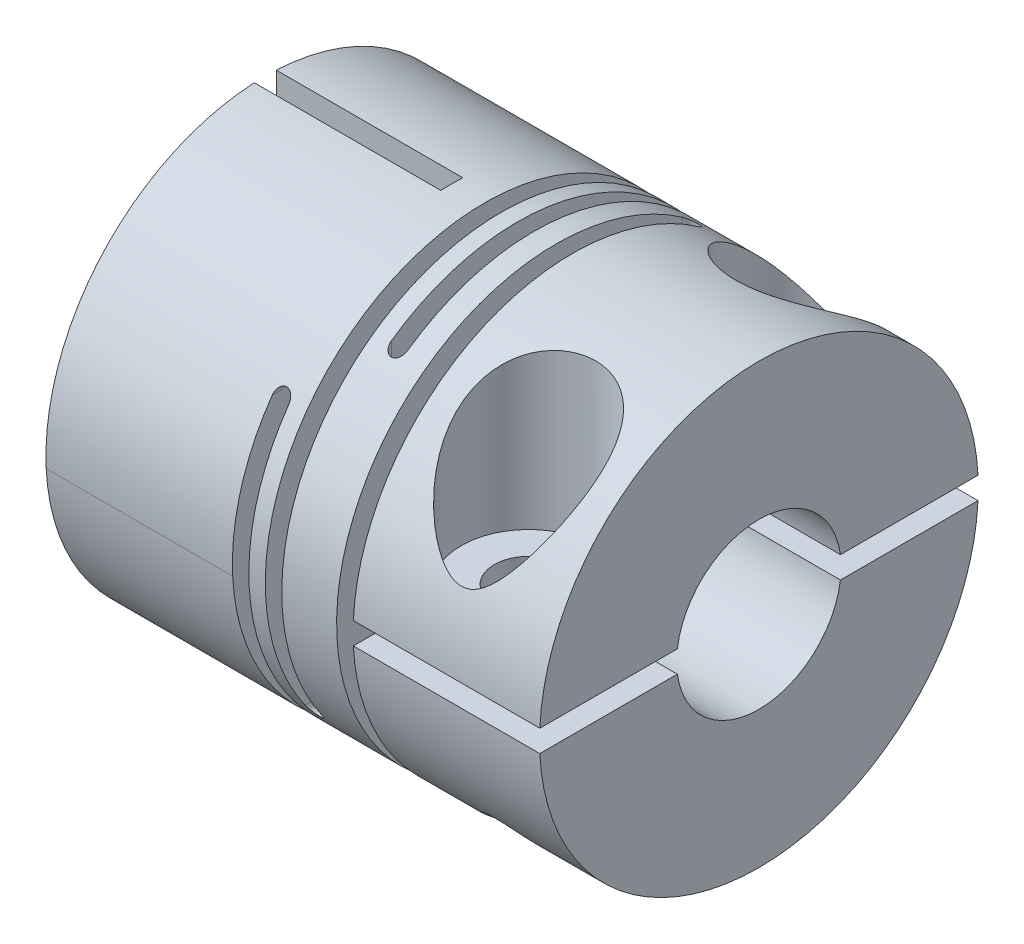
SolidWorks part; units mm, degrees
ref_plane "前视基准面" through (0, 0, 0) normal (0, 0, 1) x (1, 0, 0)
ref_plane "上视基准面" through (0, 0, 0) normal (0, 1, 0) x (1, 0, 0)
ref_plane "右视基准面" through (0, 0, 0) normal (1, 0, 0) x (0, 0, -1)
other "Configuration Table"
sketch "草图6" plane through (0, 0, 0) normal (1, 0, 0) x (0, 0, -1)
  circle A0 centre (0, 0) radius 8
  dimension "D1" = 16
extrude "凸台-拉伸4" add sketch "草图6" along normal blind 18
sketch "草图8" plane through (0, 0, 0) normal (0, 0, 1) x (1, 0, 0)
  line L0 (7.1, 4.6) -> (7.1, -8.7196) construction
  line L1 (7.4, 4.6) -> (7.4, -8.7196)
  line L2 (6.8, 4.6) -> (6.8, -8.7196)
  line L3 (8.3, 9.9177) -> (8.3, -4.6) construction
  line L4 (8.6, 9.9177) -> (8.6, -4.6)
  line L5 (8, 9.9177) -> (8, -4.6)
  line L6 (0, 8) -> (0, -8) construction
  line L7 (0, 0) -> (20.3451, 0) construction
  arc A0 (7.4, 4.6) -> (6.8, 4.6) centre (7.1, 4.6) ccw
  arc A1 (6.8, -8.7196) -> (7.4, -8.7196) centre (7.1, -8.7196) ccw
  arc A2 (8.6, 9.9177) -> (8, 9.9177) centre (8.3, 9.9177) ccw
  arc A3 (8, -4.6) -> (8.6, -4.6) centre (8.3, -4.6) ccw
  point P2 (7.1, -2.0598)
  point P9 (8.3, 2.6589)
  dimension "D1" = 6.8
  dimension "D2" = 0.6
  dimension "D3" = 0.6
  dimension "D4" = 1.2
  dimension "D5" = 4.6
  dimension "D6" = 4.6
extrude "切除-拉伸1" cut sketch "草图8" against normal through all both and the other way through all
sketch "草图9" plane through (0, 0, 0) normal (0, 1, 0) x (1, 0, 0)
  line L0 (0, 0) -> (19.4872, 0) construction
  line L1 (9.5, 9.7846) -> (9.5, -4.6) construction
  line L2 (9.8, 9.7846) -> (9.8, -4.6)
  line L3 (9.2, 9.7846) -> (9.2, -4.6)
  line L4 (10.9, 4.6) -> (10.9, -8.9267) construction
  line L5 (11.2, 4.6) -> (11.2, -8.9267)
  line L6 (10.6, 4.6) -> (10.6, -8.9267)
  line L7 (18, -8) -> (18, 8) construction
  arc A0 (9.8, 9.7846) -> (9.2, 9.7846) centre (9.5, 9.7846) ccw
  arc A1 (9.2, -4.6) -> (9.8, -4.6) centre (9.5, -4.6) ccw
  arc A2 (11.2, 4.6) -> (10.6, 4.6) centre (10.9, 4.6) ccw
  arc A3 (10.6, -8.9267) -> (11.2, -8.9267) centre (10.9, -8.9267) ccw
  point P5 (9.5, 2.5923)
  point P12 (10.9, -2.1633)
  dimension "D1" = 0.6
  dimension "D2" = 0.6
  dimension "D3" = 4.6
  dimension "D4" = 4.6
  dimension "D5" = 6.8
  dimension "D6" = 1.4
extrude "切除-拉伸2" cut sketch "草图9" against normal through all both and the other way through all
sketch "草图10" plane through (0, 0, 0) normal (0, 0, 1) x (1, 0, 0)
  line L0 (0, 0) -> (19.2209, 0) construction
  line L1 (11.2, 8) -> (11.2, -8) construction
  line L2 (11.2, 0.4) -> (18, 0.4)
  line L3 (11.2, 0.4) -> (11.2, -0.4)
  line L4 (11.2, -0.4) -> (18, -0.4)
  line L5 (18, 0.4) -> (18, -0.4)
  line L6 (18, -8) -> (18, 8) construction
  dimension "D1" = 0.8
extrude "切除-拉伸3" cut sketch "草图10" against normal through all both and the other way through all
sketch "草图11" plane through (0, 0, 0) normal (0, 1, 0) x (1, 0, 0)
  line L0 (0, 0) -> (13.7629, 0) construction
  line L1 (0, 8) -> (0, -8) construction
  line L2 (0, 0.4) -> (6.8, 0.4)
  line L3 (0, 0.4) -> (0, -0.4)
  line L4 (0, -0.4) -> (6.8, -0.4)
  line L5 (6.8, 0.4) -> (6.8, -0.4)
  line L6 (6.8, 6.5452) -> (6.8, -6.5452) construction
  dimension "D1" = 0.8
extrude "切除-拉伸4" cut sketch "草图11" against normal through all both and the other way through all
sketch "草图12" plane through (0, 0, 0) normal (-1, 0, 0) x (0, 0, 1)
  circle A0 centre (0, 0) radius 2.5
  dimension "D1" = 5
extrude "切除-拉伸6" cut sketch "草图12" against normal up to vertex (6.8 mm away)
sketch "草图14" plane through (18, 0, 0) normal (1, 0, 0) x (0, 0, -1)
  circle A0 centre (0, 0) radius 3
  dimension "D1" = 6
extrude "切除-拉伸7" cut sketch "草图14" against normal up to vertex (6.8 mm away)
ref_plane "基准面3" through (0, 8, 0) normal (0, 1, 0) x (1, 0, 0)
hole_wizard "M2.5 六角圆柱头螺钉的柱形沉头孔2" positions "草图23" profile "草图24" counterbore size "M2.5" standard "GB" end condition up to next
sketch "草图23" plane through (0, 8, 0) normal (0, 1, 0) x (1, 0, 0)
  line L0 (0, 0) -> (24.0341, 0) construction
  line L4 (18, -7.99) -> (18, 7.99) construction
  point P0 (14.6, 5)
  point P2 (14.6, -5)
  point P14 (14.6622, 7.99)
  point P21 (17.8838, 5.6541)
  point P24 (0, 0)
  dimension "D1" = 10
  dimension "D2" = 3.4
sketch "草图24" plane through (14.6, 8, -5) normal (1, 0, 0) x (0, 0, 1)
  line L0 (0, 0) -> (0, 7.6)
  line L1 (0, 7.6) -> (1.25, 7.6)
  line L3 (1.25, 7.6) -> (1.25, 6.25)
  line L4 (2.45, 6.25) -> (1.25, 6.25)
  line L5 (2.45, 6.25) -> (2.45, 0.075)
  line L6 (2.45, 0.075) -> (2.525, 0)
  line L7 (2.525, 0) -> (0, 0)
  line L8 (-2.45, 0.075) -> (-2.525, 0) construction
  line L11 (0, -6.35) -> (0, 107.95) construction
  dimension "通孔孔直径" = 2.5
  dimension "通孔孔深度" = 7.6
  dimension "柱形沉头孔直径" = 4.9
  dimension "柱形沉头孔深度" = 6.25
  dimension "近端锥形沉头孔直径" = 5.05
  dimension "近端锥形沉头孔角度" = 90
ref_plane "基准面4" through (0, -8, 0) normal (0, -1, 0) x (-1, 0, 0)
hole_wizard "M2.5 螺纹孔1" positions "草图25" profile "草图26" tap size "M2.5" standard "GB" end condition up to next
sketch "草图25" plane through (0, -8, 0) normal (0, -1, 0) x (-1, 0, 0)
  point P0 (-14.6, 5)
  point P3 (-14.6, -5)
sketch "草图26" plane through (14.6, -8, -5) normal (1, 0, 0) x (0, 0, -1)
  line L0 (0, 0) -> (0, 7.6)
  line L1 (0, 7.6) -> (1.025, 7.6)
  line L2 (1.025, 7.6) -> (1.025, 0.25)
  line L3 (1.025, 0.25) -> (1.275, 0)
  line L5 (1.275, 0) -> (0, 0)
  line L6 (-1.025, 0.25) -> (-1.275, 0) construction
  line L11 (0, -6.35) -> (0, 107.95) construction
  dimension "通孔螺纹孔钻头直径" = 2.05
  dimension "通孔螺纹孔钻头深度" = 7.6
  dimension "近端锥形沉头孔直径" = 2.55
  dimension "近端锥形沉头孔角度" = 90
cosmetic thread "孔螺纹线1"
cosmetic thread "孔螺纹线2"
sketch "草图27" plane through (0, -8, 0) normal (0, -1, 0) x (-1, 0, 0)
  circle A0 centre (-14.6, 5) radius 1.25
  circle A1 centre (-14.6, -5) radius 1.25
  dimension "D1" = 2.5
  dimension "D2" = 2.5
extrude "切除-拉伸9" cut sketch "草图27" against normal offset from surface (3.75 mm away) 3.85 up to face at (14.6, -0.4, -6.025)
